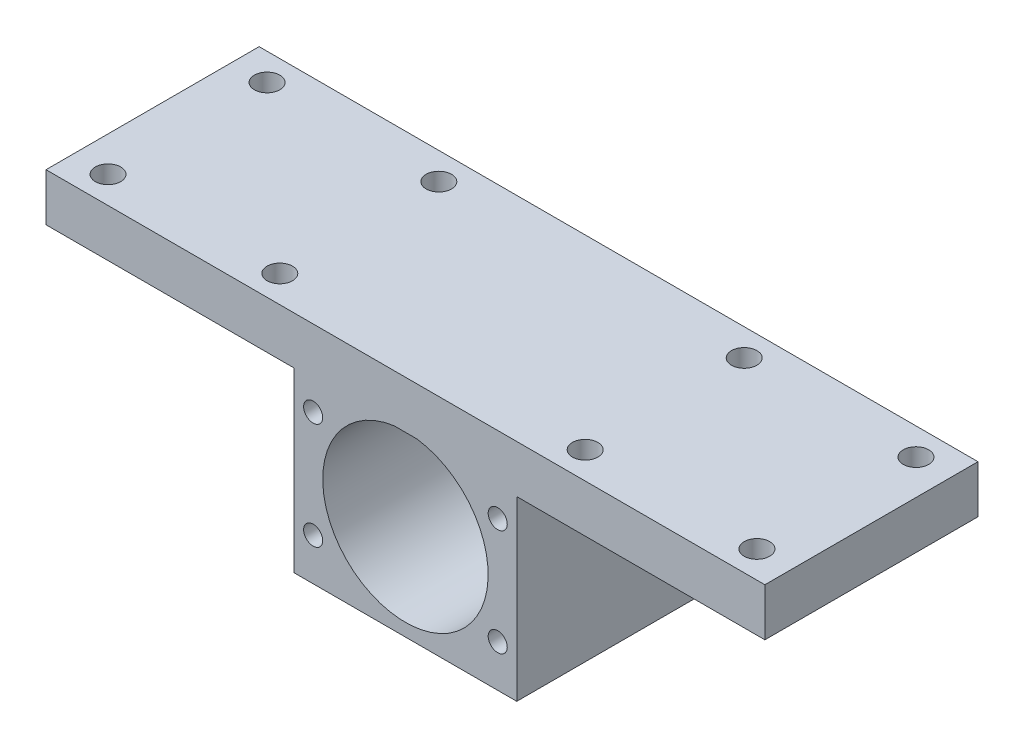
SolidWorks part; units mm, degrees
material "6061-T6 (SS)"
ref_plane "Front" through (0, 0, 0) normal (0, 0, 1) x (1, 0, 0)
ref_plane "Top" through (0, 0, 0) normal (0, 1, 0) x (1, 0, 0)
ref_plane "Right" through (0, 0, 0) normal (1, 0, 0) x (0, 0, -1)
sketch "Sketch1" plane through (0, 0, 0) normal (0, 1, 0) x (1, 0, 0)
  line L0 (-102, -25) -> (-48, -25) construction
  line L1 (-102, -25) -> (-102, 25) construction
  line L2 (-102, 25) -> (-48, 25) construction
  line L3 (-48, -25) -> (-48, 25) construction
  line L4 (-37, 33.5) -> (-113, 33.5)
  line L5 (-37, 33.5) -> (-37, -33.5) construction
  line L6 (-37, -33.5) -> (-113, -33.5)
  line L7 (-113, 33.5) -> (-113, -33.5)
  line L8 (-37, 33.5) -> (-113, -33.5) construction
  line L9 (-37, -33.5) -> (-113, 33.5) construction
  line L10 (-102, -25) -> (-48, 25) construction
  line L11 (-102, 25) -> (-48, -25) construction
  line L12 (0, 0) -> (0, 17.6116) construction
  line L13 (75, 0) -> (-75, 0) construction
  line L14 (102, 25) -> (48, -25) construction
  line L15 (102, -25) -> (48, 25) construction
  line L16 (37, -33.5) -> (113, 33.5) construction
  line L17 (37, 33.5) -> (113, -33.5) construction
  line L18 (48, -25) -> (48, 25) construction
  line L19 (102, 25) -> (48, 25) construction
  line L20 (102, -25) -> (102, 25) construction
  line L21 (102, -25) -> (48, -25) construction
  line L22 (113, 33.5) -> (113, -33.5)
  line L23 (37, -33.5) -> (113, -33.5)
  line L24 (37, 33.5) -> (37, -33.5) construction
  line L25 (37, 33.5) -> (113, 33.5)
  line L26 (-37, 33.5) -> (37, 33.5)
  line L27 (-37, -33.5) -> (37, -33.5)
  circle A0 centre (-102, 25) radius 4
  circle A1 centre (-48, 25) radius 4
  circle A2 centre (-102, -25) radius 4
  circle A3 centre (-48, -25) radius 4
  circle A4 centre (48, -25) radius 4
  circle A5 centre (102, -25) radius 4
  circle A6 centre (48, 25) radius 4
  circle A7 centre (102, 25) radius 4
  point P4 (-75, 0)
  point P9 (-75, 0)
  point P31 (75, 0)
  point P32 (75, 0)
  point P37 (-172.0912, 33.5)
  dimension "D5" = 8
  dimension "D1" = 50
  dimension "D2" = 54
  dimension "D3" = 76
  dimension "D4" = 67
  dimension "D6" = 226
extrude "Boss-Extrude1" add sketch "Sketch1" along normal blind 15
sketch "Sketch2" plane through (0, 0, 33.5) normal (0, 0, 1) x (1, 0, 0)
  line L0 (-35, -25.75) -> (35, -25.75) construction
  line L1 (-35, 4.25) -> (35, 4.25)
  line L2 (-35, 4.25) -> (-35, -55.75)
  line L3 (-35, -55.75) -> (35, -55.75)
  line L4 (35, 4.25) -> (35, -55.75)
  line L5 (113, 0) -> (-113, 0) construction
  line L6 (113, 0) -> (-113, 0)
  line L7 (29.0119, -42.5) -> (29.0119, -9) construction
  line L8 (29.0119, -42.5) -> (-29.0119, -42.5) construction
  line L9 (-29.0119, -42.5) -> (-29.0119, -9) construction
  line L10 (29.0119, -9) -> (-29.0119, -9) construction
  line L11 (29.0119, -42.5) -> (-29.0119, -9) construction
  line L12 (-29.0119, -42.5) -> (29.0119, -9) construction
  circle A0 centre (0, -25.75) radius 26
  circle A1 centre (-29.0119, -9) radius 3
  circle A2 centre (-29.0119, -42.5) radius 3
  circle A3 centre (29.0119, -42.5) radius 3
  circle A4 centre (29.0119, -9) radius 3
  point P11 (0, -25.75)
  line M1 (-113, 0) -> (113, 0)
  dimension "D1" = 52
  dimension "D7" = 6
  dimension "D2" = 25.75
  dimension "D3" = 60
  dimension "D4" = 70
  dimension "D5" = 58.0237
  dimension "D6" = 33.5
extrude "Boss-Extrude3" add sketch "Sketch2" against normal up to surface (67 mm away) contours L2 L0 A0 M1 | A0 L0 L4 M1 | L0 L2 L3 L4 A0 up to face at (0, 7.5, -33.5)
